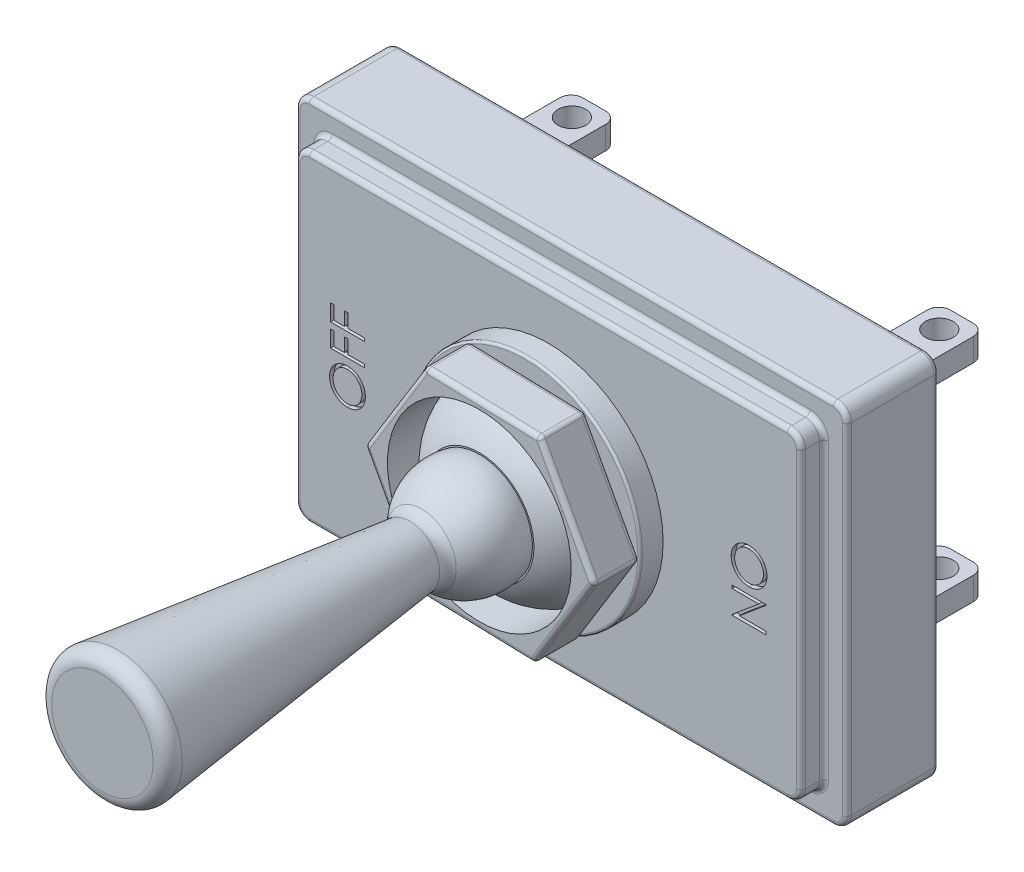
SolidWorks part; units mm, degrees
ref_plane "Front Plane" through (0, 0, 0) normal (0, 0, 1) x (1, 0, 0)
ref_plane "Top Plane" through (0, 0, 0) normal (0, 1, 0) x (1, 0, 0)
ref_plane "Right Plane" through (0, 0, 0) normal (1, 0, 0) x (0, 0, -1)
sketch "Sketch1" plane through (0, 0, 0) normal (0, 0, 1) x (1, 0, 0)
  line L1 (-60, -40) -> (60, -40)
  line L2 (-60, -40) -> (-60, 40)
  line L3 (-60, 40) -> (60, 40)
  line L4 (60, -40) -> (60, 40)
  line L5 (-60, -40) -> (60, 40) construction
  line L6 (-60, 40) -> (60, -40) construction
  point P0 (0, 0)
  dimension "D1" = 120
  dimension "D2" = 80
extrude "Boss-Extrude1" add sketch "Sketch1" along normal mid plane 20
sketch "Sketch2" plane through (0, 0, 10) normal (0, 0, 1) x (1, 0, 0)
  line L0 (-55, 35) -> (-55, -35)
  line L1 (-55, -35) -> (55, -35)
  line L2 (55, -35) -> (55, 35)
  line L3 (55, 35) -> (-55, 35)
  line L4 (60, -40) -> (60, 40)
  line L5 (60, 40) -> (-60, 40)
  line L6 (-60, 40) -> (-60, -40)
  line L7 (-60, -40) -> (60, -40)
  line L8 (60, -40) -> (60, 40) construction
  line L9 (60, 40) -> (-60, 40) construction
  line L10 (-60, 40) -> (-60, -40) construction
  line L11 (-60, -40) -> (60, -40) construction
  dimension "D1" = 0
  dimension "D2" = 5
extrude "Boss-Extrude2" add sketch "Sketch2" along normal blind 5
mirror "Mirror1" about plane through (0, 0, 0) normal (0, 0, 1) of "Boss-Extrude2"
fillet "Fillet1" radius 3 12 edges at (-55, 35, -12.5) (55, 35, -12.5) (55, -35, -12.5) (-55, -35, -12.5) (-55, -35, 12.5) (-55, 35, 12.5) (55, 35, 12.5) (55, -35, 12.5) (60, -40, 0) (-60, -40, 0) (-60, 40, 0) (60, 40, 0)
sketch "Sketch3" plane through (0, 0, 15) normal (0, 0, 1) x (1, 0, 0)
  circle A0 centre (0, 0) radius 25
  circle A1 centre (0, 0) radius 20
  dimension "D1" = 50
  dimension "D2" = 5
extrude "Boss-Extrude3" add sketch "Sketch3" along normal blind 5
sketch "Sketch4" plane through (0, 0, 20) normal (0, 0, 1) x (1, 0, 0)
  line L1 (13.1246, 21.2778) -> (-11.8648, 22.0051)
  line L2 (-11.8648, 22.0051) -> (-24.9894, 0.7274)
  line L3 (-24.9894, 0.7274) -> (-13.1246, -21.2778)
  line L4 (-13.1246, -21.2778) -> (11.8648, -22.0051)
  line L5 (11.8648, -22.0051) -> (24.9894, -0.7274)
  line L6 (24.9894, -0.7274) -> (13.1246, 21.2778)
  circle A0 centre (0, 0) radius 21.6506 construction
  circle A1 centre (0, 0) radius 20
extrude "Boss-Extrude4" add sketch "Sketch4" along normal blind 10 separate body
sketch "Sketch5" plane through (0, 0, 0) normal (0, 1, 0) x (1, 0, 0)
  line L0 (0, 0) -> (0, -112.035) construction
  line L1 (13.1246, -20) -> (-11.8648, -20) construction
  line L2 (6.3146, -43.4805) -> (14.4219, -112.035)
  line L3 (14.4219, -112.035) -> (0, -112.035)
  line L4 (0, -112.035) -> (0, -20)
  arc A0 (0, -20) -> (6.3146, -43.4805) centre (-1.0495, -32.8716) cw
revolve "Revolve1" add sketch "Sketch5" angle 360 about L0
fillet "Fillet2" radius 3 1 edges at (-14.4219, 0, 112.035)
fillet "Fillet3" radius 3 1 edges at (-6.3146, 0, 43.4805)
sketch "Sketch6" plane through (0, 0, 0) normal (0, 1, 0) x (1, 0, 0)
  line L0 (0, 0) -> (0, -68.6994) construction
  line L2 (11.8648, -30) -> (11.5415, -30)
  line L5 (3.6615, -20) -> (20, -20)
  line L6 (3.6615, -20) -> (3.6615, -20.8472)
  arc A0 (11.8648, -30) -> (20, -20) centre (5.9253, -16.8591) ccw
  arc A1 (7.504, -42.5472) -> (0, -20) centre (-1.0495, -32.8716) ccw construction
  arc A2 (11.5415, -30) -> (3.6615, -20.8472) centre (-1.0495, -32.8716) ccw
revolve "Revolve4" add sketch "Sketch6" angle 360 about L0
sketch "Sketch7" plane through (0, 0, -15) normal (0, 0, -1) x (-1, 0, 0)
  line L0 (0, 0) -> (0, -68.9185) construction
  line L1 (-55, -32) -> (-55, 32) construction
  line L2 (-45, 25) -> (-35, 25)
  line L3 (-45, 25) -> (-45, 20)
  line L4 (-45, 20) -> (-35, 20)
  line L5 (-35, 25) -> (-35, 20)
  line L6 (-52, 35) -> (52, 35) construction
  line L7 (0, 0) -> (88.0157, 0) construction
  line L8 (-35, -25) -> (-35, -20)
  line L9 (-45, -25) -> (-35, -25)
  line L10 (-45, -25) -> (-45, -20)
  line L11 (-45, -20) -> (-35, -20)
  line L12 (45, 20) -> (35, 20)
  line L13 (45, 25) -> (45, 20)
  line L14 (45, 25) -> (35, 25)
  line L15 (35, 25) -> (35, 20)
  line L16 (45, -20) -> (35, -20)
  line L17 (45, -25) -> (45, -20)
  line L18 (45, -25) -> (35, -25)
  line L19 (35, -25) -> (35, -20)
  dimension "D1" = 5
  dimension "D2" = 10
  dimension "D3" = 10
  dimension "D4" = 10
extrude "Boss-Extrude5" add sketch "Sketch7" along normal blind 20 separate body
sketch "Sketch8" plane through (0, 25, 0) normal (0, 1, 0) x (1, 0, 0)
  circle A0 centre (-40, 30.1364) radius 3.0211
  circle A1 centre (39.9625, 30.1364) radius 3.0211
extrude "Cut-Extrude1" cut sketch "Sketch8" against normal blind 78
sketch "Sketch9" plane through (0, 0, 15) normal (0, 0, 1) x (1, 0, 0)
  line L0 (40, 15) -> (40, -15) construction
  line L1 (0, 0) -> (69.641, 0) construction
  line L2 (55, -32) -> (55, 32) construction
  line L3 (0, 0) -> (0, -55.5254) construction
  line L4 (-40, 15) -> (-40, -15) construction
  text T0 "  ON" font "Century Gothic" height in points 28
  text T1 "     OFF  " font "Century Gothic" height in points 28
  point P5 (40, 0)
  point P8 (0, -55.5254)
  dimension "D1" = 15
  dimension "D2" = 30
extrude "Cut-Extrude2" cut sketch "Sketch9" against normal blind 1
fillet "Fillet4" radius 1 32 edges at (59.1213, 39.1213, -10) (0, 40, -10) (-59.1213, 39.1213, -10) (-60, 0, -10) (-59.1213, -39.1213, -10) (0, -40, -10) (59.1213, -39.1213, -10) (60, 0, -10) (54.1213, -34.1213, -10) (0, -35, -10) (-54.1213, -34.1213, -10) (-55, 0, -10) (-54.1213, 34.1213, -10) (0, 35, -10) (54.1213, 34.1213, -10) (55, 0, -10) (-54.1213, 34.1213, 10) (-55, 0, 10) (-54.1213, -34.1213, 10) (0, -35, 10) (54.1213, -34.1213, 10) (55, 0, 10) (54.1213, 34.1213, 10) (0, 35, 10) (-59.1213, -39.1213, 10) (-60, 0, 10) (-59.1213, 39.1213, 10) (0, 40, 10) (59.1213, 39.1213, 10) (60, 0, 10) (59.1213, -39.1213, 10) (0, -40, 10)
fillet "Fillet5" radius 0.5 1 edges at (25, 0, 20)
fillet "Fillet6" radius 2.5 2 edges at (-35, 22.5, -35) (-45, 22.5, -35)
fillet "Fillet7" radius 2.5 2 edges at (-35, -22.5, -35) (-45, -22.5, -35)
fillet "Fillet8" radius 2.5 2 edges at (35, 22.5, -35) (45, 22.5, -35)
fillet "Fillet9" radius 2.5 2 edges at (45, -22.5, -35) (35, -22.5, -35)
sketch "Sketch10" plane through (0, 0, -15) normal (0, 0, -1) x (-1, 0, 0)
  line L0 (-46, 26) -> (-46, 19)
  line L1 (-45, 25) -> (-35, 25)
  line L2 (-45, 25) -> (-45, 20)
  line L3 (-45, 20) -> (-35, 20)
  line L4 (-35, 25) -> (-35, 20)
  line L5 (-46, 19) -> (-34, 19)
  line L6 (-34, 26) -> (-34, 19)
  line L7 (-46, 26) -> (-34, 26)
  line L8 (-59, 0) -> (0, 0) construction
  line L9 (-59, 37) -> (-59, -37) construction
  line L10 (0, 0) -> (0, 51.4529) construction
  line L11 (-34, -26) -> (-34, -19)
  line L12 (-35, -25) -> (-35, -20)
  line L13 (-46, -26) -> (-34, -26)
  line L14 (-45, -25) -> (-35, -25)
  line L15 (-45, -25) -> (-45, -20)
  line L16 (-46, -26) -> (-46, -19)
  line L17 (-45, -20) -> (-35, -20)
  line L18 (-46, -19) -> (-34, -19)
  line L19 (46, -26) -> (46, -19)
  line L20 (45, -25) -> (45, -20)
  line L21 (46, -19) -> (34, -19)
  line L22 (45, -20) -> (35, -20)
  line L23 (45, -25) -> (35, -25)
  line L24 (46, -26) -> (34, -26)
  line L25 (35, -25) -> (35, -20)
  line L26 (34, -26) -> (34, -19)
  line L27 (46, 26) -> (46, 19)
  line L28 (45, 25) -> (45, 20)
  line L29 (45, 25) -> (35, 25)
  line L30 (45, 20) -> (35, 20)
  line L31 (46, 19) -> (34, 19)
  line L32 (46, 26) -> (34, 26)
  line L33 (35, 25) -> (35, 20)
  line L34 (34, 26) -> (34, 19)
  dimension "D1" = 1
extrude "Boss-Extrude6" add sketch "Sketch10" along normal blind 2
fillet "Fillet10" radius 0.5 16 edges at (-34, 22.5, -15) (-40, 26, -15) (-46, 22.5, -15) (-40, 19, -15) (-46, -22.5, -15) (-40, -26, -15) (-34, -22.5, -15) (-40, -19, -15) (40, -19, -15) (46, -22.5, -15) (34, -22.5, -15) (40, -26, -15) (40, 26, -15) (34, 22.5, -15) (40, 19, -15) (46, 22.5, -15)
fillet "Fillet11" radius 1 18 edges at (-18.4271, 11.3663, 30) (-18.4271, 11.3663, 20) (0.6299, 21.6415, 30) (-11.8648, 22.0051, 25) (0.6299, 21.6415, 20) (19.057, 10.2752, 30) (13.1246, 21.2778, 25) (19.057, 10.2752, 20) (18.4271, -11.3663, 30) (24.9894, -0.7274, 25) (18.4271, -11.3663, 20) (-0.6299, -21.6415, 30) (11.8648, -22.0051, 25) (-0.6299, -21.6415, 20) (-24.9894, 0.7274, 25) (-19.057, -10.2752, 30) (-13.1246, -21.2778, 25) (-19.057, -10.2752, 20)
fillet "Fillet12" radius 1 16 edges at (-54.1213, -34.1213, -15) (-55, 0, -15) (-54.1213, 34.1213, -15) (0, 35, -15) (54.1213, 34.1213, -15) (55, 0, -15) (54.1213, -34.1213, -15) (-54.1213, -34.1213, 15) (-55, 0, 15) (-54.1213, 34.1213, 15) (0, 35, 15) (54.1213, 34.1213, 15) (55, 0, 15) (54.1213, -34.1213, 15) (0, -35, -15) (0, -35, 15)
